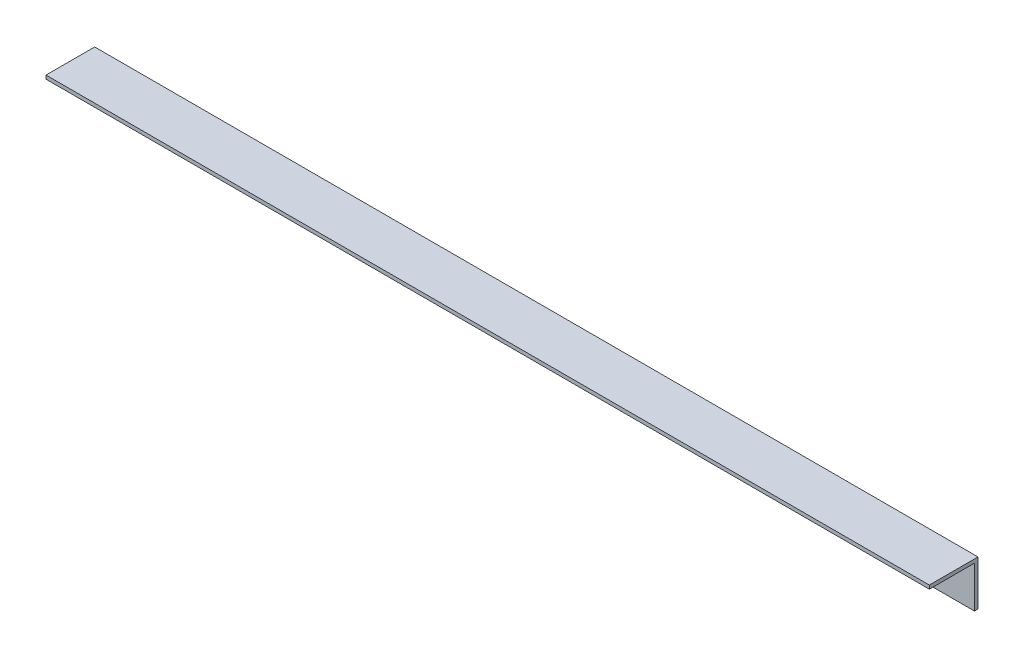
SolidWorks part; units mm, degrees
ref_plane "前视" through (0, 0, 0) normal (0, 0, 1) x (1, 0, 0)
ref_plane "上视" through (0, 0, 0) normal (0, 1, 0) x (1, 0, 0)
ref_plane "右视" through (0, 0, 0) normal (1, 0, 0) x (0, 0, -1)
sketch "草图1" plane through (0, 0, 0) normal (0, 0, 1) x (1, 0, 0)
  line L0 (0, 0) -> (0, 145.6903) construction
  line L1 (-980, 94.5121) -> (980, 94.5121)
  line L2 (-980, 94.5121) -> (-980, -5.4879)
  line L3 (-980, -5.4879) -> (980, -5.4879)
  line L4 (980, 94.5121) -> (980, -5.4879)
  line L5 (930, 34.5121) -> (-270, 34.5121) construction
  dimension "D1" = 1960
  dimension "D2" = 100
  dimension "D4" = 40
  dimension "D5" = 50
  dimension "D9" = 94.5121
extrude "基体-拉伸" add sketch "草图1" along normal blind 8
sketch "草图2" plane through (0, 0, 8) normal (0, 0, 1) x (1, 0, 0)
  line L0 (0, 0) -> (0, 140.4626) construction
  line L3 (-980, 94.5121) -> (980, 94.5121)
  line L4 (-980, 94.5121) -> (-980, 86.5121)
  line L5 (-980, 86.5121) -> (980, 86.5121)
  line L6 (980, 94.5121) -> (980, 86.5121)
  dimension "D1" = 1960
  dimension "D2" = 8
extrude "凸台-拉伸1" add sketch "草图2" along normal blind 100
